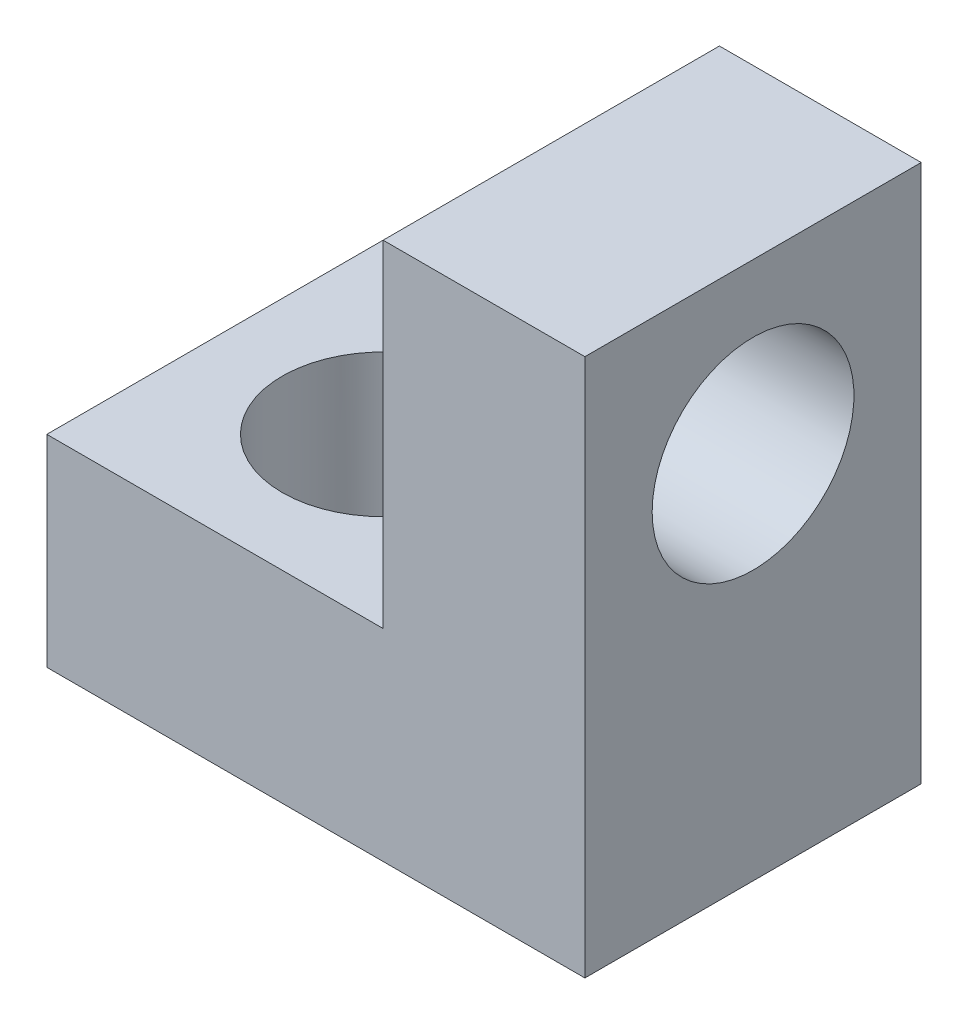
SolidWorks part; units mm, degrees
ref_plane "Front Plane" through (0, 0, 0) normal (0, 0, 1) x (1, 0, 0)
ref_plane "Top Plane" through (0, 0, 0) normal (0, 1, 0) x (1, 0, 0)
ref_plane "Right Plane" through (0, 0, 0) normal (1, 0, 0) x (0, 0, -1)
sketch "Sketch1" plane through (0, 0, 0) normal (0, 1, 0) x (1, 0, 0)
  line L1 (-4, -2.5) -> (4, -2.5)
  line L2 (-4, -2.5) -> (-4, 2.5)
  line L3 (-4, 2.5) -> (4, 2.5)
  line L4 (4, -2.5) -> (4, 2.5)
  line L5 (-4, -2.5) -> (4, 2.5) construction
  line L6 (-4, 2.5) -> (4, -2.5) construction
  point P0 (0, 0)
  dimension "D1" = 8
  dimension "D2" = 5
extrude "Boss-Extrude1" add sketch "Sketch1" along normal blind 3
sketch "Sketch2" plane through (0, 3, 0) normal (0, 1, 0) x (1, 0, 0)
  line L0 (-4, -2.5) -> (4, -2.5) construction
  line L1 (4, 2.5) -> (1, 2.5)
  line L2 (4, 2.5) -> (4, -2.5)
  line L3 (4, -2.5) -> (1, -2.5)
  line L4 (1, 2.5) -> (1, -2.5)
  dimension "D1" = 3
extrude "Boss-Extrude2" add sketch "Sketch2" along normal blind 5
sketch "Sketch3" plane through (0, 3, 0) normal (0, 1, 0) x (1, 0, 0)
  line L0 (1, 2.5) -> (-4, 2.5) construction
  line L1 (-4, 2.5) -> (-4, -2.5) construction
  circle A0 centre (-1.5, 0) radius 1.5
  dimension "D3" = 3
  dimension "D1" = 2.5
  dimension "D2" = 2.5
extrude "Cut-Extrude1" cut sketch "Sketch3" against normal blind 5
sketch "Sketch4" plane through (1, 0, 0) normal (-1, 0, 0) x (0, 0, 1)
  line L0 (2.5, 8) -> (2.5, 3) construction
  line L1 (-2.5, 3) -> (2.5, 3) construction
  circle A0 centre (0, 5.5) radius 1.5
  dimension "D3" = 3
  dimension "D1" = 2.5
  dimension "D2" = 2.5
extrude "Cut-Extrude2" cut sketch "Sketch4" against normal blind 5
